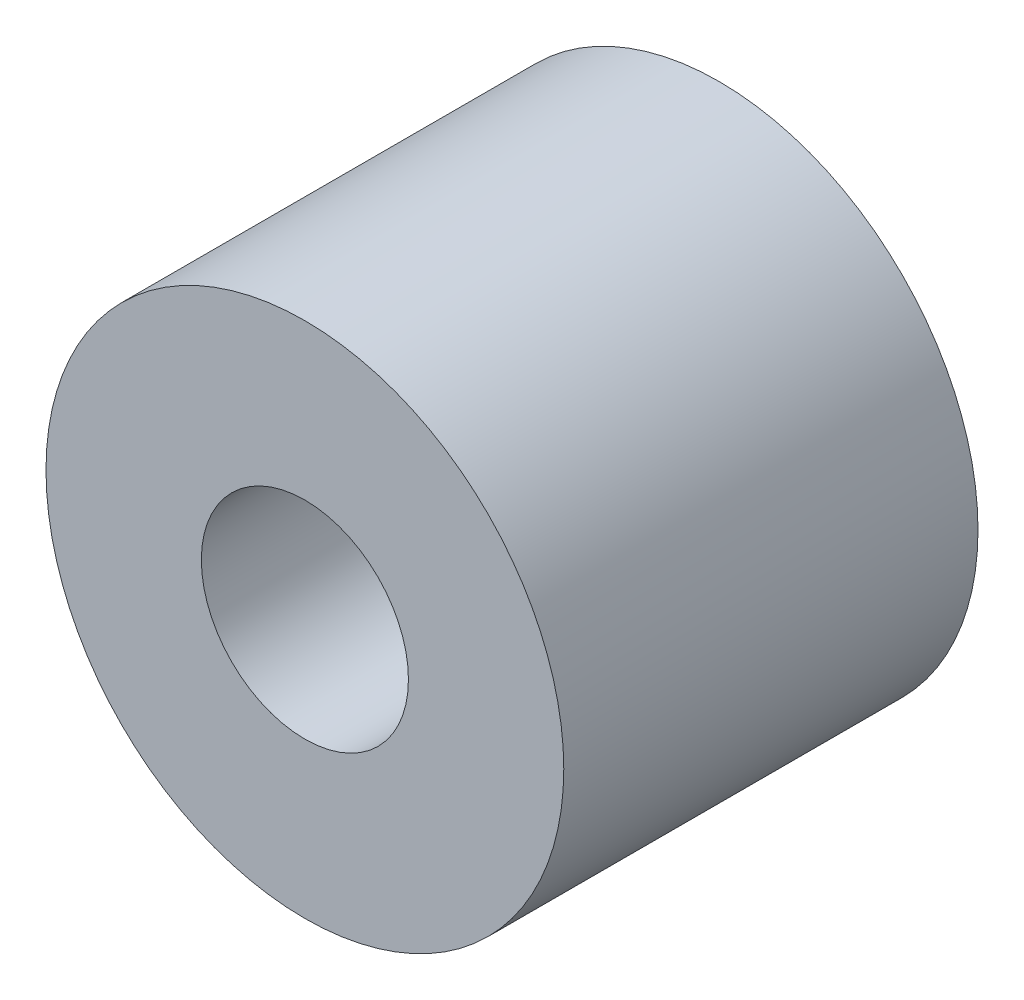
SolidWorks part; units mm, degrees
material "Beech"
ref_plane "Front Plane" through (0, 0, 0) normal (0, 0, 1) x (1, 0, 0)
ref_plane "Top Plane" through (0, 0, 0) normal (0, 1, 0) x (1, 0, 0)
ref_plane "Right Plane" through (0, 0, 0) normal (1, 0, 0) x (0, 0, -1)
sketch "Sketch1" plane through (0, 0, 0) normal (0, 0, 1) x (1, 0, 0)
  circle A0 centre (0, 0) radius 10
  circle A1 centre (0, 0) radius 25
  dimension "D1" = 20
  dimension "D2" = 50
extrude "Boss-Extrude1" add sketch "Sketch1" along normal blind 40
